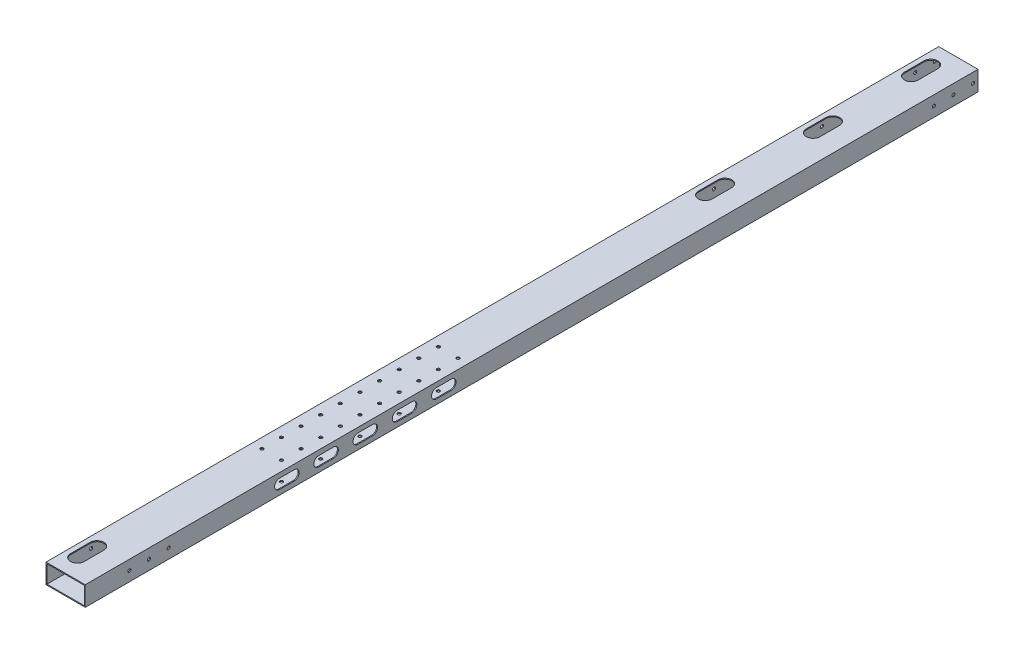
SolidWorks part; units mm, degrees
material "1060 合金"
ref_plane "前视基准面" through (0, 0, 0) normal (0, 0, 1) x (1, 0, 0)
ref_plane "上视基准面" through (0, 0, 0) normal (0, 1, 0) x (1, 0, 0)
ref_plane "右视基准面" through (0, 0, 0) normal (1, 0, 0) x (0, 0, -1)
other "Configuration Table"
sketch "草图1" plane through (0, 0, 0) normal (0, 0, 1) x (1, 0, 0)
  line L1 (-40, 20) -> (0, 20)
  line L2 (-40, 20) -> (-40, 0)
  line L3 (-40, 0) -> (0, 0)
  line L4 (0, 20) -> (0, 0)
  dimension "D1" = 20
  dimension "D2" = 40
extrude "拉伸-薄壁1" add sketch "草图1" along normal blind 910 thin
sketch "草图2" plane through (-40, 0, 0) normal (-1, 0, 0) x (0, 0, 1)
  circle A0 centre (865, 10) radius 1.6 construction
  circle A1 centre (845, 10) radius 1.6 construction
  circle A2 centre (825, 10) radius 1.6 construction
  circle A3 centre (45, 10) radius 1.6 construction
  circle A4 centre (25, 10) radius 1.6 construction
  circle A5 centre (5, 10) radius 1.6 construction
  circle A6 centre (865, 10) radius 1.6
  circle A7 centre (845, 10) radius 1.6
  circle A8 centre (825, 10) radius 1.6
  circle A9 centre (45, 10) radius 1.6
  circle A10 centre (25, 10) radius 1.6
  circle A11 centre (5, 10) radius 1.6
extrude "切除-拉伸1" cut sketch "草图2" against normal blind 70
sketch "草图3" plane through (-40, 0, 0) normal (-1, 0, 0) x (0, 0, 1)
  line L0 (0, 20) -> (0, 0) construction
  line L1 (910, 0) -> (0, 0) construction
  circle A0 centre (120, 10) radius 1.6
  circle A1 centre (140, 10) radius 1.6
  circle A2 centre (230, 10) radius 1.6
  circle A3 centre (250, 10) radius 1.6
  dimension "D3" = 3.2
  dimension "D4" = 3.2
  dimension "D1" = 120
  dimension "D2" = 20
  dimension "D5" = 10
  dimension "D6" = 10
  dimension "D7" = 2
extrude "切除-拉伸2" cut sketch "草图3" against normal blind 10
sketch "草图4" plane through (0, 0, 0) normal (0, -1, 0) x (1, 0, 0)
  line L0 (-28, 140) -> (-28, 120) construction
  line L1 (-22, 140) -> (-22, 120)
  line L2 (-34, 140) -> (-34, 120)
  line L3 (-40, 0) -> (0, 0) construction
  line L4 (-40, 910) -> (-40, 0) construction
  line L5 (-28, 250) -> (-28, 230) construction
  line L6 (-22, 250) -> (-22, 230)
  line L7 (-34, 250) -> (-34, 230)
  arc A0 (-22, 140) -> (-34, 140) centre (-28, 140) ccw
  arc A1 (-34, 120) -> (-22, 120) centre (-28, 120) ccw
  arc A2 (-22, 250) -> (-34, 250) centre (-28, 250) ccw
  arc A3 (-34, 230) -> (-22, 230) centre (-28, 230) ccw
  point P2 (-28, 130)
  point P15 (-28, 240)
  dimension "D2" = 6
  dimension "D1" = 20
  dimension "D3" = 120
  dimension "D4" = 12
  dimension "D5" = 2
extrude "切除-拉伸3" [suppressed] cut sketch "草图4" against normal up to next
sketch "草图5" plane through (0, 20, 0) normal (0, 1, 0) x (1, 0, 0)
  line L0 (-28, -120) -> (-28, -140) construction
  line L1 (-21, -120) -> (-21, -140)
  line L2 (-35, -120) -> (-35, -140)
  line L3 (-40, -910) -> (-40, 0) construction
  line L4 (0, 0) -> (-40, 0) construction
  line L5 (-28, -230) -> (-28, -250) construction
  line L6 (-21, -230) -> (-21, -250)
  line L7 (-35, -230) -> (-35, -250)
  line L8 (-28, -20) -> (-28, -40) construction
  line L9 (-21, -20) -> (-21, -40)
  line L10 (-35, -20) -> (-35, -40)
  line L11 (-28, -870) -> (-28, -890) construction
  line L12 (-21, -870) -> (-21, -890)
  line L13 (-35, -870) -> (-35, -890)
  arc A0 (-21, -120) -> (-35, -120) centre (-28, -120) ccw
  arc A1 (-35, -140) -> (-21, -140) centre (-28, -140) ccw
  arc A2 (-21, -230) -> (-35, -230) centre (-28, -230) ccw
  arc A3 (-35, -250) -> (-21, -250) centre (-28, -250) ccw
  arc A4 (-21, -20) -> (-35, -20) centre (-28, -20) ccw
  arc A5 (-35, -40) -> (-21, -40) centre (-28, -40) ccw
  arc A6 (-21, -870) -> (-35, -870) centre (-28, -870) ccw
  arc A7 (-35, -890) -> (-21, -890) centre (-28, -890) ccw
  point P2 (-28, -130)
  point P14 (-28, -240)
  point P21 (-28, -30)
  point P29 (-28, -880)
  dimension "D2" = 7
  dimension "D1" = 12
  dimension "D3" = 120
  dimension "D4" = 20
  dimension "D5" = 2
  dimension "D6" = 2
  dimension "D7" = 2
extrude "切除-拉伸4" cut sketch "草图5" against normal blind 10
sketch "草图6" plane through (0, 20, 0) normal (0, 1, 0) x (1, 0, 0)
  line L0 (-40, -910) -> (-40, 0) construction
  line L1 (0, -910) -> (-40, -910) construction
  circle A0 centre (-30, -700) radius 1.6
  circle A1 centre (-10, -700) radius 1.6
  circle A2 centre (-10, -680) radius 1.6
  circle A3 centre (-10, -660) radius 1.6
  circle A4 centre (-10, -640) radius 1.6
  circle A5 centre (-10, -620) radius 1.6
  circle A6 centre (-10, -600) radius 1.6
  circle A7 centre (-10, -580) radius 1.6
  circle A8 centre (-10, -560) radius 1.6
  circle A9 centre (-10, -540) radius 1.6
  circle A10 centre (-10, -520) radius 1.6
  circle A11 centre (-30, -680) radius 1.6
  circle A12 centre (-30, -660) radius 1.6
  circle A13 centre (-30, -640) radius 1.6
  circle A14 centre (-30, -620) radius 1.6
  circle A15 centre (-30, -600) radius 1.6
  circle A16 centre (-30, -580) radius 1.6
  circle A17 centre (-30, -560) radius 1.6
  circle A18 centre (-30, -540) radius 1.6
  circle A19 centre (-30, -520) radius 1.6
  dimension "D1" = 3.2
  dimension "D2" = 10
  dimension "D3" = 210
  dimension "D4" = 2
  dimension "D5" = 10
extrude "切除-拉伸5" cut sketch "草图6" against normal through all
sketch "草图7" plane through (0, 0, 0) normal (1, 0, 0) x (0, 0, -1)
  line L0 (-712, 10) -> (-697, 10) construction
  line L1 (-712, 15) -> (-697, 15)
  line L2 (-712, 5) -> (-697, 5)
  line L3 (-910, 0) -> (0, 0) construction
  line L4 (-910, 0) -> (-910, 20) construction
  line L5 (-672, 10) -> (-657, 10) construction
  line L6 (-672, 15) -> (-657, 15)
  line L7 (-672, 5) -> (-657, 5)
  line L8 (-632, 10) -> (-617, 10) construction
  line L9 (-632, 15) -> (-617, 15)
  line L10 (-632, 5) -> (-617, 5)
  line L11 (-592, 10) -> (-577, 10) construction
  line L12 (-592, 15) -> (-577, 15)
  line L13 (-592, 5) -> (-577, 5)
  line L14 (-552, 10) -> (-537, 10) construction
  line L15 (-552, 15) -> (-537, 15)
  line L16 (-552, 5) -> (-537, 5)
  arc A0 (-712, 15) -> (-712, 5) centre (-712, 10) ccw
  arc A1 (-697, 5) -> (-697, 15) centre (-697, 10) ccw
  arc A2 (-672, 15) -> (-672, 5) centre (-672, 10) ccw
  arc A3 (-657, 5) -> (-657, 15) centre (-657, 10) ccw
  arc A4 (-632, 15) -> (-632, 5) centre (-632, 10) ccw
  arc A5 (-617, 5) -> (-617, 15) centre (-617, 10) ccw
  arc A6 (-592, 15) -> (-592, 5) centre (-592, 10) ccw
  arc A7 (-577, 5) -> (-577, 15) centre (-577, 10) ccw
  arc A8 (-552, 15) -> (-552, 5) centre (-552, 10) ccw
  arc A9 (-537, 5) -> (-537, 15) centre (-537, 10) ccw
  point P2 (-704.5, 10)
  point P14 (-664.5, 10)
  point P21 (-624.5, 10)
  point P28 (-584.5, 10)
  point P35 (-544.5, 10)
  dimension "D2" = 5
  dimension "D1" = 10
  dimension "D3" = 198
  dimension "D4" = 15
  dimension "D5" = 5
extrude "切除-拉伸6" cut sketch "草图7" against normal up to next
